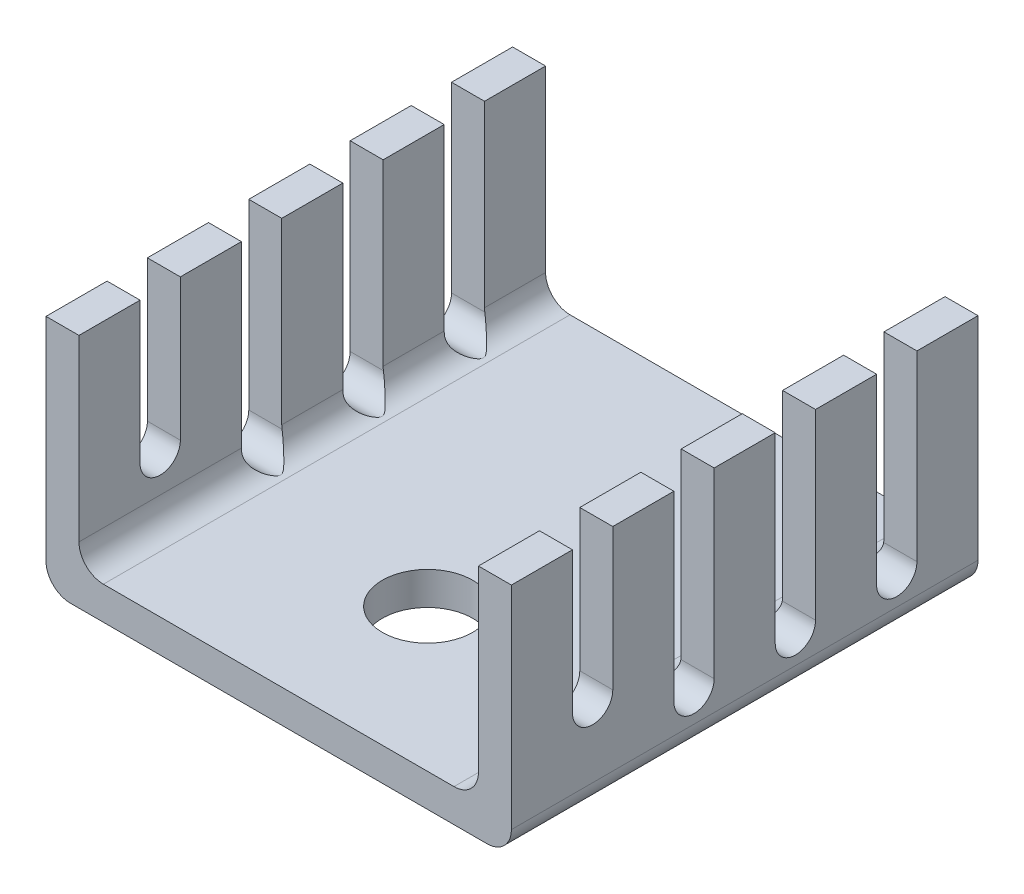
SolidWorks part; units mm, degrees
ref_plane "Front Plane" through (0, 0, 0) normal (0, 0, 1) x (1, 0, 0)
ref_plane "Top Plane" through (0, 0, 0) normal (0, 1, 0) x (1, 0, 0)
ref_plane "Right Plane" through (0, 0, 0) normal (1, 0, 0) x (0, 0, -1)
sketch "Sketch1" plane through (0, 0, 0) normal (0, 0, 1) x (1, 0, 0)
  line L0 (-8.525, 0) -> (8.525, 0)
  line L1 (9.525, 1) -> (9.525, 9.67)
  line L2 (9.525, 9.67) -> (8.175, 9.67)
  line L3 (8.175, 9.67) -> (8.175, 2.35)
  line L4 (7.175, 1.35) -> (-7.175, 1.35)
  line L5 (-8.175, 2.35) -> (-8.175, 9.67)
  line L6 (-8.175, 9.67) -> (-9.525, 9.67)
  line L7 (-9.525, 9.67) -> (-9.525, 1)
  arc A0 (-7.175, 1.35) -> (-8.175, 2.35) centre (-7.175, 2.35) cw
  arc A1 (8.175, 2.35) -> (7.175, 1.35) centre (7.175, 2.35) cw
  arc A2 (8.525, 0) -> (9.525, 1) centre (8.525, 1) ccw
  arc A3 (-8.525, 0) -> (-9.525, 1) centre (-8.525, 1) cw
  point P10 (0, 0)
  point P19 (9.525, 0)
  point P22 (-9.525, 0)
  dimension "D5" = 1
  dimension "D6" = 1
  dimension "D1" = 19.05
  dimension "D2" = 9.67
  dimension "D3" = 1.35
  dimension "D4" = 1.35
extrude "Boss-Extrude3" add sketch "Sketch1" against normal blind 19.1
sketch "Sketch3" plane through (0, 1.35, 0) normal (0, 1, 0) x (1, 0, 0)
  circle A0 centre (0.2414, 5.85) radius 1.85
  dimension "D2" = 3.7
  dimension "D1" = 5.85
extrude "Cut-Extrude2" cut sketch "Sketch3" against normal up to next
sketch "Sketch4" plane through (9.525, 0, 0) normal (1, 0, 0) x (0, 0, -1)
  line L0 (2.5, 9.67) -> (2.5, 3.88)
  line L1 (19.1, 0) -> (0, 0) construction
  line L2 (19.1, 9.67) -> (0, 9.67) construction
  line L3 (4.15, 9.67) -> (4.15, 3.88)
  line L4 (6.65, 9.67) -> (6.65, 2.2)
  line L5 (8.3, 9.67) -> (8.3, 2.2)
  line L6 (10.8, 9.67) -> (10.8, 2.2)
  line L7 (12.45, 9.67) -> (12.45, 2.2)
  line L8 (14.95, 9.67) -> (14.95, 2.2)
  line L9 (16.6, 9.67) -> (16.6, 2.2)
  line L10 (19.1, 1) -> (19.1, 9.67) construction
  line L11 (2.5, 9.67) -> (4.15, 9.67)
  line L12 (6.65, 9.67) -> (8.3, 9.67)
  line L13 (10.8, 9.67) -> (12.45, 9.67)
  line L14 (14.95, 9.67) -> (16.6, 9.67)
  arc A1 (2.5, 3.88) -> (4.15, 3.88) centre (3.325, 3.88) ccw
  arc A2 (6.65, 2.2) -> (8.3, 2.2) centre (7.475, 2.2) ccw
  arc A3 (10.8, 2.2) -> (12.45, 2.2) centre (11.625, 2.2) ccw
  arc A4 (14.95, 2.2) -> (16.6, 2.2) centre (15.775, 2.2) ccw
  dimension "D9" = 3.88
  dimension "D10" = 2.2
  dimension "D1" = 1.65
  dimension "D2" = 1.65
  dimension "D3" = 1.65
  dimension "D4" = 1.65
  dimension "D5" = 2.5
  dimension "D6" = 2.5
  dimension "D7" = 2.5
  dimension "D8" = 2.5
extrude "Cut-Extrude3" cut sketch "Sketch4" against normal through all
